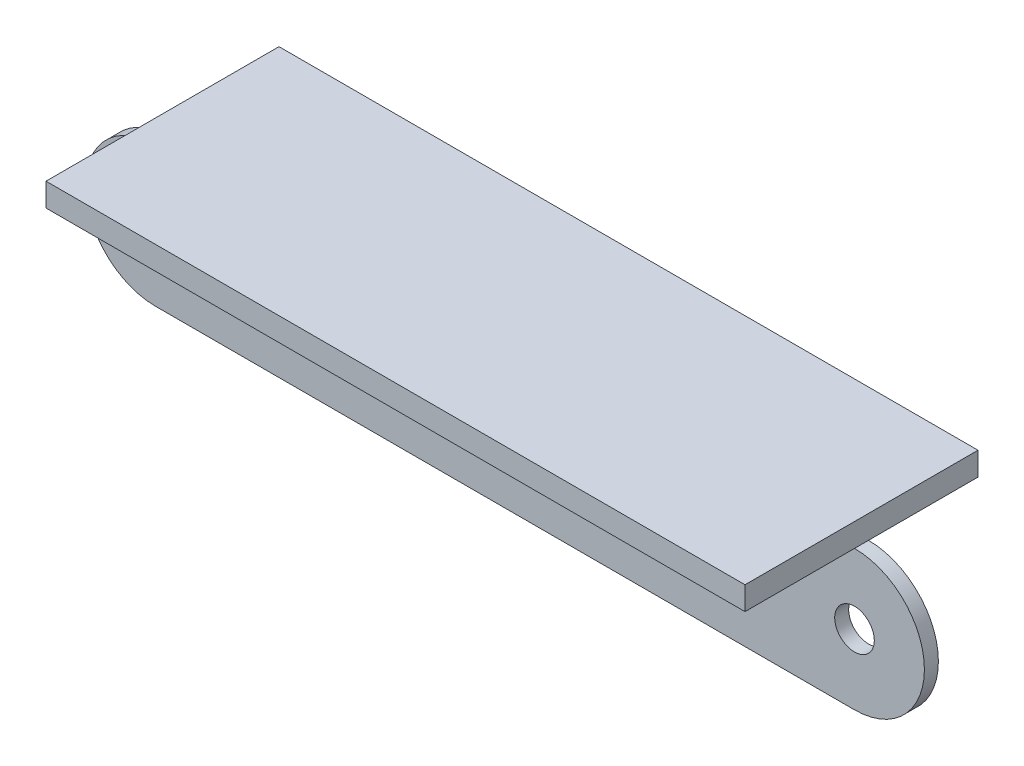
SolidWorks part; units mm, degrees
ref_plane "Plano frontal" through (0, 0, 0) normal (0, 0, 1) x (1, 0, 0)
ref_plane "Plano superior" through (0, 0, 0) normal (0, 1, 0) x (1, 0, 0)
ref_plane "Plano direito" through (0, 0, 0) normal (1, 0, 0) x (0, 0, -1)
sketch "Esboço1" plane through (0, 0, 0) normal (0, 0, 1) x (1, 0, 0)
  line L0 (64.7929, 11.1834) -> (-85.2071, 11.1834) construction
  line L1 (-85.2071, 26.1834) -> (64.7929, 26.1834)
  line L3 (-85.2071, -3.8166) -> (64.7929, -3.8166)
  arc A0 (64.7929, 26.1834) -> (64.7929, -3.8166) centre (64.7929, 11.1834) cw
  arc A1 (-85.2071, -3.8166) -> (-85.2071, 26.1834) centre (-85.2071, 11.1834) cw
  circle A3 centre (-85.2071, 11.1834) radius 4.25
  circle A4 centre (64.7929, 11.1834) radius 4.25
  dimension "D3" = 8.5
  dimension "D4" = 8.5
  dimension "D1" = 150
  dimension "D2" = 30
extrude "Ressalto-extrusão1" add sketch "Esboço1" along normal blind 3
sketch "Esboço2" plane through (0, 26.1834, 0) normal (0, 1, 0) x (1, 0, 0)
  line L0 (64.7929, -3) -> (64.7929, 0) construction
  line L1 (-85.2071, 23.5) -> (64.7929, 23.5)
  line L2 (-85.2071, 23.5) -> (-85.2071, -26.5)
  line L3 (-85.2071, -26.5) -> (64.7929, -26.5)
  line L4 (64.7929, 23.5) -> (64.7929, -26.5)
  line L5 (-85.2071, -3) -> (-85.2071, 0) construction
  dimension "D1" = 0
  dimension "D2" = 0
  dimension "D3" = 23.5
  dimension "D4" = 23.5
  dimension "D5" = 50
extrude "Ressalto-extrusão2" add sketch "Esboço2" along normal blind 5
sketch "Esboço3" plane through (-85.2071, 0, 0) normal (-1, 0, 0) x (0, 0, 1)
  line L0 (3, 19.6834) -> (9.5, 26.1834)
  line L1 (3, -3.8166) -> (3, 26.1834) construction
  line L2 (3, 26.1834) -> (26.5, 26.1834) construction
  line L3 (9.5, 26.1834) -> (3, 26.1834)
  line L4 (3, 26.1834) -> (3, 19.6834)
  line L5 (0, 26.1834) -> (0, 19.6834)
  line L6 (0, 26.1834) -> (0, -3.8166) construction
  line L7 (0, 19.6834) -> (-6.5, 26.1834)
  line L8 (-23.5, 26.1834) -> (0, 26.1834) construction
  line L9 (-6.5, 26.1834) -> (0, 26.1834)
  dimension "D1" = 6.5
  dimension "D2" = 6.5
  dimension "D3" = 6.5
extrude "Ressalto-extrusão3" add sketch "Esboço3" against normal blind 100 from offset 25
